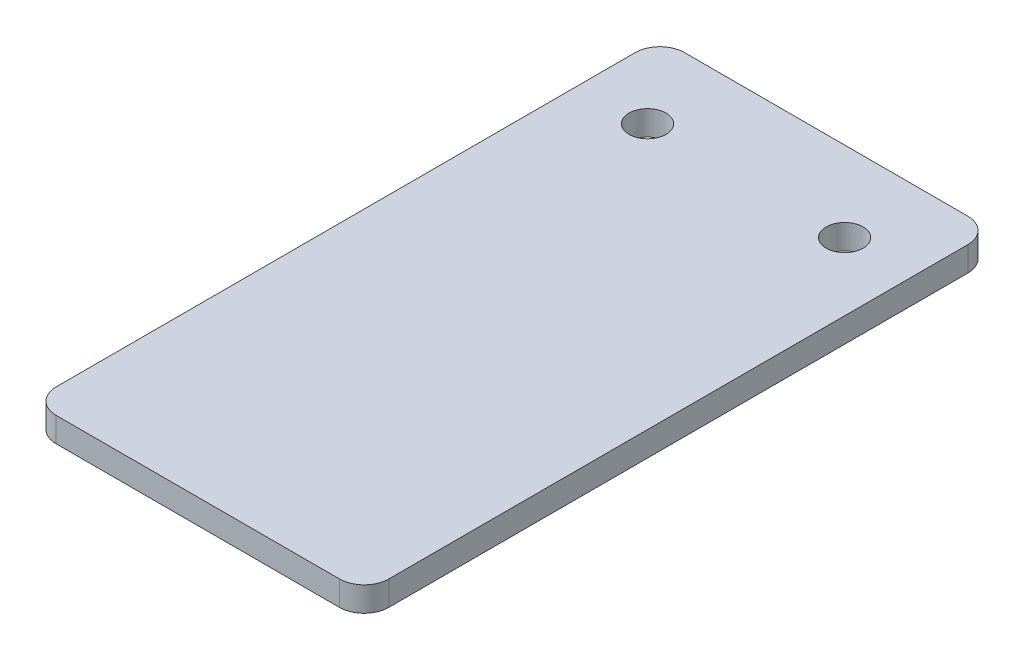
SolidWorks part; units mm, degrees
ref_plane "Front Plane" through (0, 0, 0) normal (0, 0, 1) x (1, 0, 0)
ref_plane "Top Plane" through (0, 0, 0) normal (0, 1, 0) x (1, 0, 0)
ref_plane "Right Plane" through (0, 0, 0) normal (1, 0, 0) x (0, 0, -1)
sketch "Sketch1" plane through (0, 0, 0) normal (0, 1, 0) x (1, 0, 0)
  line L0 (0, 25.5) -> (27, 25.5) construction
  line L1 (2, 0) -> (25, 0)
  line L2 (0, 2) -> (0, 49)
  line L3 (2, 51) -> (25, 51)
  line L4 (27, 2) -> (27, 49)
  line L5 (13.5, 51) -> (13.5, 0) construction
  arc A2 (2, 0) -> (0, 2) centre (2, 2) cw
  arc A3 (25, 0) -> (27, 2) centre (25, 2) ccw
  arc A4 (25, 51) -> (27, 49) centre (25, 49) cw
  arc A5 (0, 49) -> (2, 51) centre (2, 49) cw
  circle A6 centre (21.5, 44.5) radius 1.5
  circle A7 centre (5.5, 44.5) radius 1.5
  point P11 (0, 0)
  point P14 (27, 0)
  point P19 (0, 51)
  dimension "D3" = 2
  dimension "D6" = 8
  dimension "D4" = 3
  dimension "D1" = 27
  dimension "D2" = 51
  dimension "D5" = 6.5
extrude "Boss-Extrude1" add sketch "Sketch1" along normal blind 2
